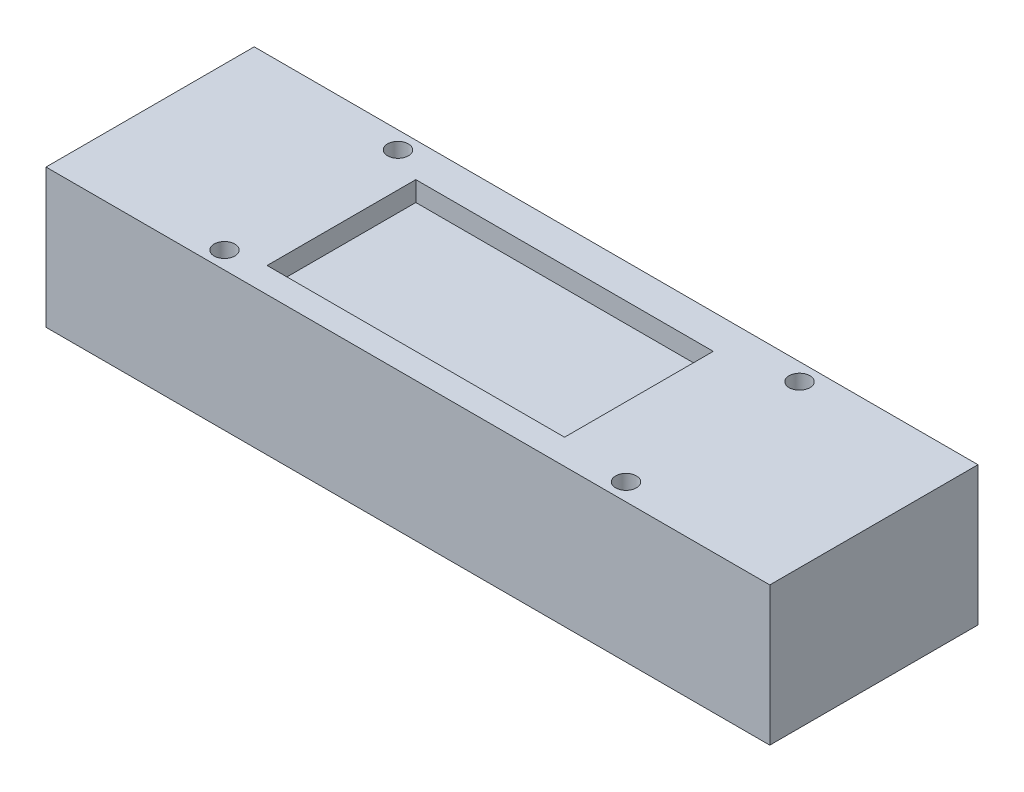
SolidWorks part; units mm, degrees
ref_plane "前视基准面" through (0, 0, 0) normal (0, 0, 1) x (1, 0, 0)
ref_plane "上视基准面" through (0, 0, 0) normal (0, 1, 0) x (1, 0, 0)
ref_plane "右视基准面" through (0, 0, 0) normal (1, 0, 0) x (0, 0, -1)
sketch "草图1" plane through (0, 0, 0) normal (0, 1, 0) x (1, 0, 0)
  line L1 (-36.5, 10.5) -> (36.5, 10.5)
  line L2 (-36.5, 10.5) -> (-36.5, -10.5)
  line L3 (-36.5, -10.5) -> (36.5, -10.5)
  line L4 (36.5, 10.5) -> (36.5, -10.5)
  line L5 (-36.5, 10.5) -> (36.5, -10.5) construction
  line L6 (-36.5, -10.5) -> (36.5, 10.5) construction
  line L7 (-20.25, 8.75) -> (20.25, 8.75) construction
  line L8 (-20.25, 8.75) -> (-20.25, -8.75) construction
  line L9 (-20.25, -8.75) -> (20.25, -8.75) construction
  line L10 (20.25, 8.75) -> (20.25, -8.75) construction
  line L11 (-20.25, 8.75) -> (20.25, -8.75) construction
  line L12 (-20.25, -8.75) -> (20.25, 8.75) construction
  circle A0 centre (-20.25, 8.75) radius 1.05
  circle A1 centre (20.25, 8.75) radius 1.05
  circle A2 centre (20.25, -8.75) radius 1.05
  circle A3 centre (-20.25, -8.75) radius 1.05
  point P0 (0, 0)
  point P6 (0, 0)
  dimension "D5" = 2.1
  dimension "D6" = 2.1
  dimension "D7" = 2.1
  dimension "D8" = 2.1
  dimension "D1" = 73
  dimension "D2" = 21
  dimension "D3" = 40.5
  dimension "D4" = 17.5
extrude "凸台-拉伸1" add sketch "草图1" along normal blind 14
ref_plane "基准面1" through (0, 14, 0) normal (0, 1, 0) x (1, 0, 0)
sketch "草图2" plane through (0, 14, 0) normal (0, 1, 0) x (1, 0, 0)
  line L1 (-16.75, 7.05) -> (13.25, 7.05)
  line L2 (-16.75, 7.05) -> (-16.75, -7.95)
  line L3 (-16.75, -7.95) -> (13.25, -7.95)
  line L4 (13.25, 7.05) -> (13.25, -7.95)
  circle A0 centre (-20.25, 8.75) radius 1.05 construction
  dimension "D1" = 30
  dimension "D2" = 15
  dimension "D3" = 3.5
  dimension "D4" = 1.7
extrude "切除-拉伸1" cut sketch "草图2" against normal blind 2
